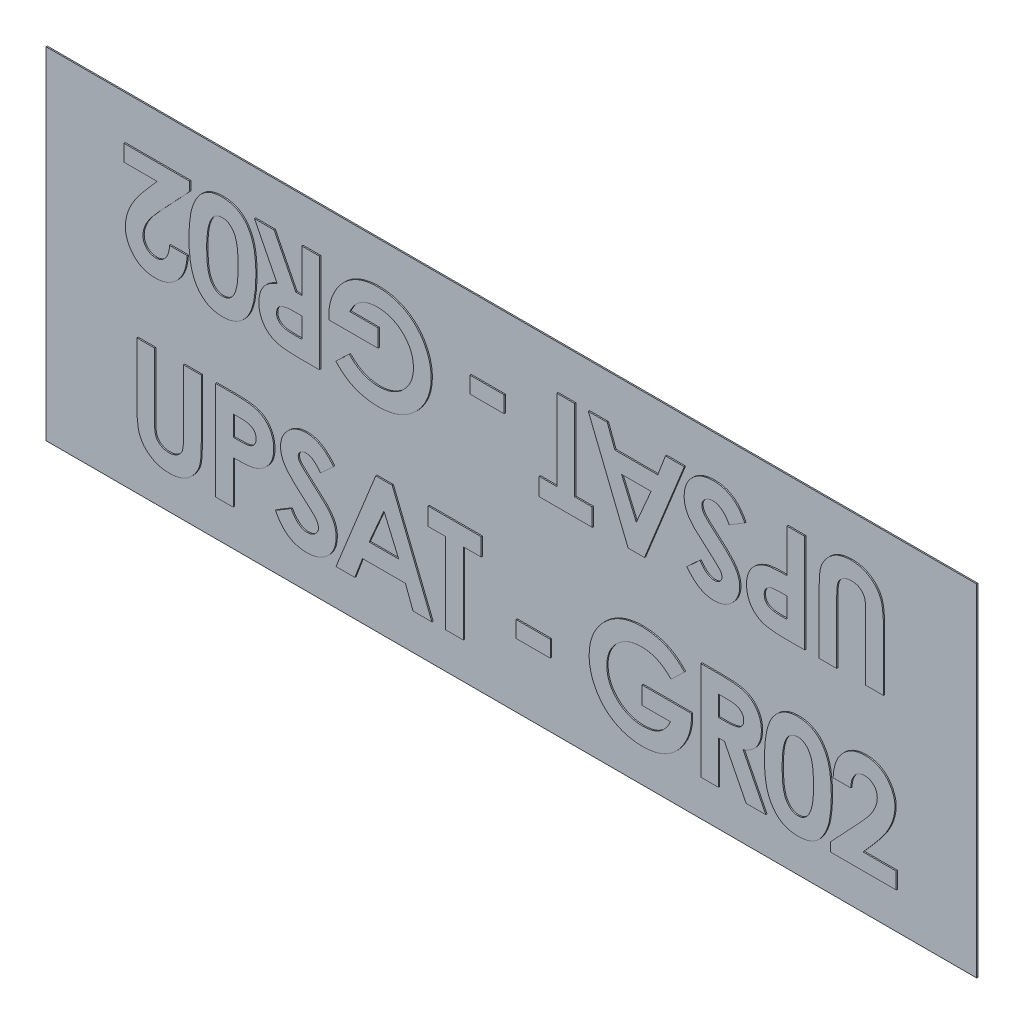
SolidWorks part; units mm, degrees
ref_plane "Front Plane" through (0, 0, 0) normal (0, 0, 1) x (1, 0, 0)
ref_plane "Top Plane" through (0, 0, 0) normal (0, 1, 0) x (1, 0, 0)
ref_plane "Right Plane" through (0, 0, 0) normal (1, 0, 0) x (0, 0, -1)
sketch "Sketch1" plane through (0, 0, 0) normal (0, 0, 1) x (1, 0, 0)
  line L1 (7.5, -2.75) -> (-7.5, -2.75)
  line L2 (7.5, -2.75) -> (7.5, 2.75)
  line L3 (7.5, 2.75) -> (-7.5, 2.75)
  line L4 (-7.5, -2.75) -> (-7.5, 2.75)
  line L5 (7.5, -2.75) -> (-7.5, 2.75) construction
  line L6 (7.5, 2.75) -> (-7.5, -2.75) construction
  point P0 (0, 0)
  dimension "D1" = 15
  dimension "D2" = 5.5
extrude "Boss-Extrude1" add sketch "Sketch1" along normal blind 0.02
sketch "Sketch2" plane through (0, 0, 0.02) normal (0, 0, 1) x (1, 0, 0)
  line L0 (-7.5, 2.75) -> (-7.5, -2.75) construction
  line L1 (-7.5, -2.75) -> (7.5, -2.75) construction
  line L2 (-7.5, 0) -> (7.5, 0) construction
  line L3 (7.5, -2.75) -> (7.5, 2.75) construction
  line L4 (7.5, 2.75) -> (-7.5, 2.75) construction
  line L5 (6.2, 2.05) -> (-7.5, 2.05) construction
  text T0 "<b>UPSAT - GR02</b>" font "Century Gothic" height in points 6
  text T1 "<b>UPSAT - GR02</b>" font "Century Gothic" height in points 6
  dimension "D1" = 1.3
  dimension "0.9" = 0.6
  dimension "D3" = 1.3
  dimension "D4" = 0.7
extrude "Boss-Extrude2" add sketch "Sketch2" along normal blind 0.02
